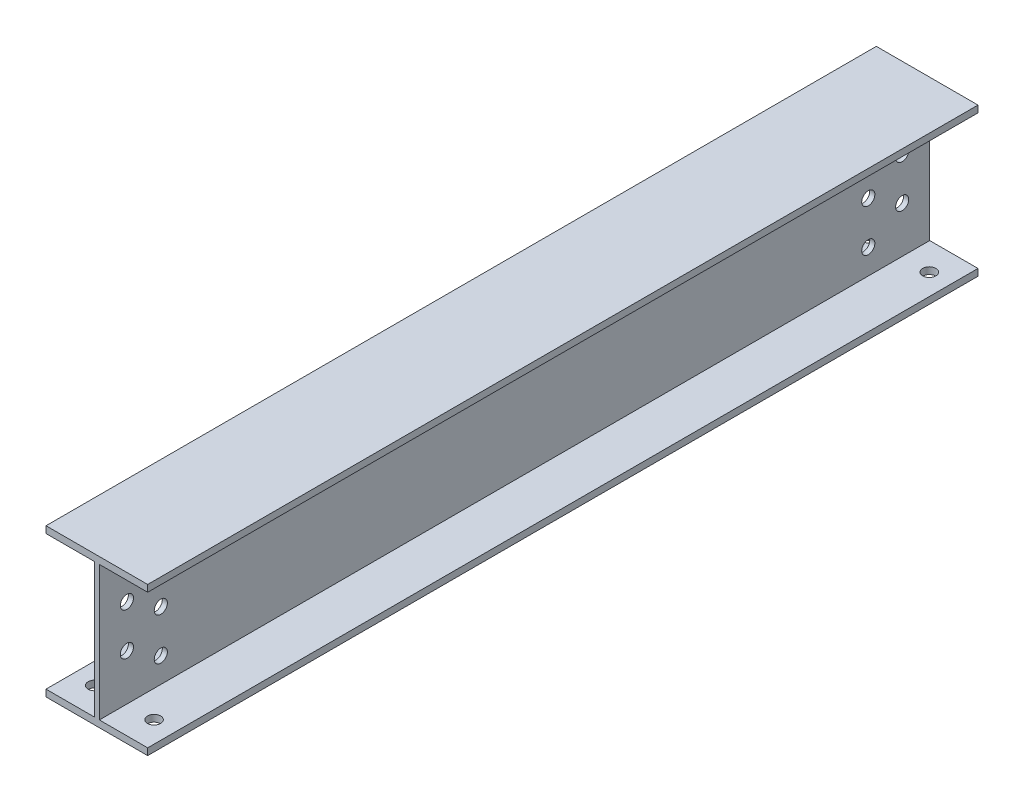
SolidWorks part; units mm, degrees
ref_plane "前视基准面" through (0, 0, 0) normal (0, 0, 1) x (1, 0, 0)
ref_plane "上视基准面" through (0, 0, 0) normal (0, 1, 0) x (1, 0, 0)
ref_plane "右视基准面" through (0, 0, 0) normal (1, 0, 0) x (0, 0, -1)
sketch "草图1" plane through (0, 0, 0) normal (0, 0, 1) x (1, 0, 0)
  line L0 (-6, 159) -> (-120, 159)
  line L1 (-120, 159) -> (-120, 175)
  line L2 (-120, 175) -> (120, 175)
  line L3 (120, 175) -> (120, 159)
  line L4 (120, 159) -> (6, 159)
  line L5 (6, 159) -> (6, -159)
  line L6 (6, -159) -> (120, -159)
  line L7 (120, -159) -> (120, -175)
  line L8 (120, -175) -> (-120, -175)
  line L9 (-120, -175) -> (-120, -159)
  line L10 (-120, -159) -> (-6, -159)
  line L11 (-6, -159) -> (-6, 159)
  line L12 (191.7545, 0) -> (-48.2455, 0) construction
  line L15 (0, 0) -> (0, 16) construction
  dimension "D1" = 350
  dimension "D2" = 240
  dimension "D3" = 12
  dimension "D4" = 16
extrude "拉伸1" add sketch "草图1" along normal mid plane 1960
sketch "草图2" plane through (0, 0, 0) normal (1, 0, 0) x (0, 0, -1)
  line L0 (-980, -159) -> (-980, 159) construction
  line L1 (-980, 175) -> (980, 175) construction
  line L3 (0, 386.6401) -> (0, -341.8233) construction
  circle A0 centre (-915, 50) radius 15.5
  circle A1 centre (-835, 100) radius 15.5
  circle A2 centre (-835, 0) radius 15.5
  circle A3 centre (-835, -100) radius 15.5
  circle A4 centre (-915, -50) radius 15.5
  circle A5 centre (915, -50) radius 15.5
  circle A6 centre (835, -100) radius 15.5
  circle A7 centre (835, 0) radius 15.5
  circle A8 centre (835, 100) radius 15.5
  circle A9 centre (915, 50) radius 15.5
  dimension "D1" = 31
  dimension "D5" = 50
  dimension "D4" = 100
  dimension "D2" = 65
  dimension "D3" = 75
  dimension "D6" = 80
  dimension "D7" = 50
  dimension "D8" = 50
extrude "拉伸2" cut sketch "草图2" against normal through all and the other way through all
sketch "草图5" plane through (0, -159, 0) normal (0, 1, 0) x (1, 0, 0)
  line L0 (0, 0) -> (0, 2071.2487) construction
  line L1 (-6, 980) -> (-120, 980) construction
  line L2 (0, 0) -> (-563.3076, 0) construction
  circle A0 centre (-70, 915) radius 15.5
  circle A1 centre (70, 915) radius 15.5
  circle A2 centre (70, -915) radius 15.5
  circle A3 centre (-70, -915) radius 15.5
  dimension "D1" = 31
  dimension "D2" = 31
  dimension "D3" = 70
  dimension "D4" = 70
  dimension "D5" = 65
extrude "拉伸4" cut sketch "草图5" against normal through all
